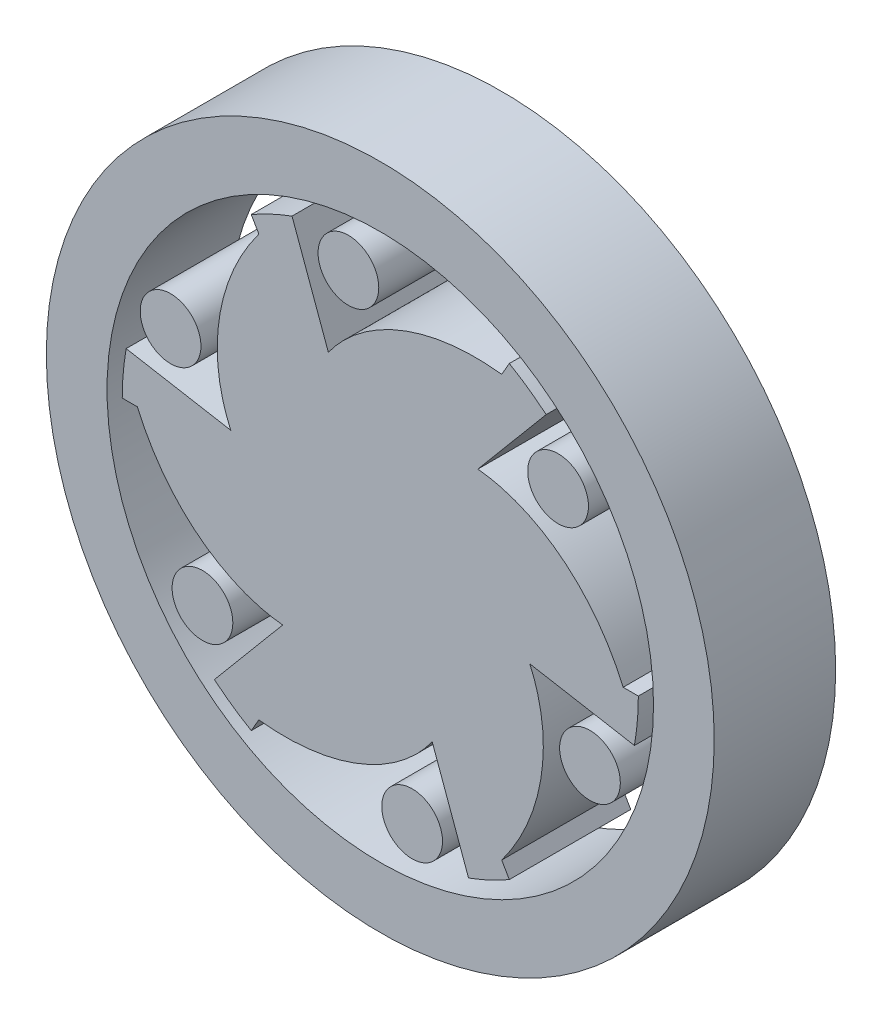
SolidWorks part; units mm, degrees
ref_plane "Front Plane" through (0, 0, 0) normal (0, 0, 1) x (1, 0, 0)
ref_plane "Top Plane" through (0, 0, 0) normal (0, 1, 0) x (1, 0, 0)
ref_plane "Right Plane" through (0, 0, 0) normal (1, 0, 0) x (0, 0, -1)
sketch "Sketch1" plane through (0, 0, 0) normal (0, 0, 1) x (1, 0, 0)
  line L5 (5.7851, 6.8944) -> (0, 0) construction
  line L9 (5.4637, 6.5114) -> (3.2139, 3.8302)
  line L10 (0, 0) -> (4.25, 7.3612)
  line L11 (8, 0) -> (0, 0)
  line L12 (5.5, 9.5263) -> (4.5, 7.7942)
  line L13 (9, 0) -> (11, 0)
  line L14 (4, -6.9282) -> (0, 0)
  line L15 (0, 0) -> (8.5, 0)
  line L16 (9, 0) -> (0, 0) construction
  line L17 (8.3709, -1.476) -> (4.924, -0.8682)
  line L18 (-4, -6.9282) -> (0, 0)
  line L19 (0, 0) -> (4.25, -7.3612)
  line L20 (2.9072, -7.9874) -> (1.7101, -4.6985)
  line L21 (-8, 0) -> (0, 0)
  line L22 (0, 0) -> (-4.25, -7.3612)
  line L23 (-5.4637, -6.5114) -> (-3.2139, -3.8302)
  line L24 (-4, 6.9282) -> (0, 0)
  line L25 (0, 0) -> (-8.5, 0)
  line L26 (-8.3709, 1.476) -> (-4.924, 0.8682)
  line L27 (4, 6.9282) -> (0, 0)
  line L28 (0, 0) -> (-4.25, 7.3612)
  line L29 (-2.9072, 7.9874) -> (-1.7101, 4.6985)
  line L30 (11, 0) -> (9, 0)
  line L31 (4.5, -7.7942) -> (5.5, -9.5263)
  line L32 (5.5, -9.5263) -> (4.5, -7.7942)
  line L33 (-4.5, -7.7942) -> (-5.5, -9.5263)
  line L34 (-5.5, -9.5263) -> (-4.5, -7.7942)
  line L35 (-9, 0) -> (-11, 0)
  line L36 (-11, 0) -> (-9, 0)
  line L37 (-4.5, 7.7942) -> (-5.5, 9.5263)
  line L38 (-5.5, 9.5263) -> (-4.5, 7.7942)
  line L39 (4.5, 7.7942) -> (5.5, 9.5263)
  circle A11 centre (5.8572, 4.594) radius 1
  circle A12 centre (5.8572, 4.594) radius 1.5 construction
  circle A13 centre (0, 0) radius 9 construction
  circle A16 centre (7.4489, 2.7445) radius 1 construction
  circle A17 centre (7.4489, 2.7445) radius 1.5 construction
  arc A18 (4.25, 7.3612) -> (5.4637, 6.5114) centre (0, 0) cw
  circle A19 centre (0, 0) radius 11 construction
  arc A20 (11, 0) -> (5.5, 9.5263) centre (0, 0) ccw
  arc A21 (4.5, 7.7942) -> (9, 0) centre (0, 0) cw
  arc A22 (8.5, 0) -> (8.3709, -1.476) centre (0, 0) cw
  circle A23 centre (6.9071, -2.7754) radius 1
  arc A24 (4.25, -7.3612) -> (2.9072, -7.9874) centre (0, 0) cw
  circle A25 centre (1.0499, -7.3694) radius 1
  arc A26 (-4.25, -7.3612) -> (-5.4637, -6.5114) centre (0, 0) cw
  circle A27 centre (-5.8572, -4.594) radius 1
  arc A28 (-8.5, 0) -> (-8.3709, 1.476) centre (0, 0) cw
  circle A29 centre (-6.9071, 2.7754) radius 1
  arc A30 (-4.25, 7.3612) -> (-2.9072, 7.9874) centre (0, 0) cw
  circle A31 centre (-1.0499, 7.3694) radius 1
  circle A32 centre (6.1012, -5.0787) radius 1.5 construction
  arc A33 (9, 0) -> (4.5, -7.7942) centre (0, 0) cw
  arc A34 (5.5, -9.5263) -> (11, 0) centre (0, 0) ccw
  circle A35 centre (-1.3477, -7.8231) radius 1.5 construction
  arc A36 (4.5, -7.7942) -> (-4.5, -7.7942) centre (0, 0) cw
  arc A37 (-5.5, -9.5263) -> (5.5, -9.5263) centre (0, 0) ccw
  circle A38 centre (-7.4489, -2.7445) radius 1.5 construction
  arc A39 (-4.5, -7.7942) -> (-9, 0) centre (0, 0) cw
  arc A40 (-11, 0) -> (-5.5, -9.5263) centre (0, 0) ccw
  circle A41 centre (-6.1012, 5.0787) radius 1.5 construction
  arc A42 (-9, 0) -> (-4.5, 7.7942) centre (0, 0) cw
  arc A43 (-5.5, 9.5263) -> (-11, 0) centre (0, 0) ccw
  circle A44 centre (1.3477, 7.8231) radius 1.5 construction
  arc A45 (-4.5, 7.7942) -> (4.5, 7.7942) centre (0, 0) cw
  arc A46 (5.5, 9.5263) -> (-5.5, 9.5263) centre (0, 0) ccw
  spline S0 degree 4 poles (8.2297, -0.6031) (8.2177, -0.5709) (8.2166, -0.5602) (8.173, -0.4439) (8.1451, -0.3547) (8.035, -0.0811) (7.9889, 0.0291) (7.8625, 0.3063) (7.7823, 0.4631) (7.676, 0.6656) (7.576, 0.8379) (7.4369, 1.0671) (7.293, 1.2812) (7.1379, 1.4954) (6.9431, 1.7408) (6.7374, 1.9796) (6.4836, 2.244) (6.1868, 2.5153) (5.9146, 2.7339) (5.6732, 2.907) (5.469, 3.0407) (5.2891, 3.1491) (5.1064, 3.2506) (4.9182, 3.3455) (4.7296, 3.4328) (4.5326, 3.5131) (4.3411, 3.5849) (4.1329, 3.65) (3.9452, 3.7046) (3.7172, 3.7543) (3.5507, 3.7891) (3.269, 3.826) (3.1429, 3.8378) (2.8808, 3.8539) (2.8076, 3.8497) (2.71, 3.8512) (2.7092, 3.8498) (2.7012, 3.8499) (2.6959, 3.85) knots 0 0 0 0 0 0.010587 0.021173 0.042347 0.084694 0.112315 0.139937 0.167558 0.19518 0.222801 0.250422 0.305665 0.333287 0.360908 0.416151 0.471394 0.526637 0.572552 0.600173 0.627794 0.655416 0.683037 0.710659 0.73828 0.765902 0.793523 0.821145 0.848766 0.876388 0.904009 0.93163 0.96246 0.993289 0.996645 0.998322 1 1 1 1 1 construction
  spline S1 degree 4 poles (8, 0) (7.9825, 0.0408) (7.9462, 0.1228) (7.8625, 0.3063) (7.7823, 0.4631) (7.676, 0.6656) (7.576, 0.8379) (7.4369, 1.0671) (7.293, 1.2812) (7.1379, 1.4954) (6.9431, 1.7408) (6.7374, 1.9796) (6.4836, 2.244) (6.1868, 2.5153) (5.9146, 2.7339) (5.6732, 2.907) (5.469, 3.0407) (5.2891, 3.1491) (5.1064, 3.2506) (4.9182, 3.3455) (4.7296, 3.4328) (4.5326, 3.5131) (4.3411, 3.5849) (4.1329, 3.65) (3.9452, 3.7046) (3.7172, 3.7543) (3.5507, 3.7891) (3.3454, 3.816) (3.2581, 3.826) (3.2139, 3.8302) knots 0.084694 0.084694 0.084694 0.084694 0.084694 0.112315 0.139937 0.167558 0.19518 0.222801 0.250422 0.305665 0.333287 0.360908 0.416151 0.471394 0.526637 0.572552 0.600173 0.627794 0.655416 0.683037 0.710659 0.73828 0.765902 0.793523 0.821145 0.848766 0.876388 0.904009 0.93163 0.93163 0.93163 0.93163 0.93163
  spline S2 degree 4 poles (3.5925, -7.4286) (3.6144, -7.4022) (3.6231, -7.3959) (3.7021, -7.3) (3.7654, -7.2312) (3.9473, -6.999) (4.0196, -6.904) (4.1965, -6.656) (4.2923, -6.5081) (4.4144, -6.3148) (4.5137, -6.1421) (4.6425, -5.907) (4.7561, -5.6753) (4.864, -5.4339) (4.9791, -5.1426) (5.0831, -4.845) (5.1851, -4.4929) (5.2717, -4.1002) (5.3249, -3.7552) (5.3542, -3.4597) (5.3678, -3.2159) (5.3717, -3.0059) (5.3683, -2.797) (5.3564, -2.5866) (5.3377, -2.3796) (5.3088, -2.1688) (5.2752, -1.9671) (5.2274, -1.7542) (5.1809, -1.5643) (5.1099, -1.3421) (5.0568, -1.1804) (4.9479, -0.9181) (4.895, -0.8029) (4.7779, -0.5679) (4.7377, -0.5066) (4.6903, -0.4214) (4.6887, -0.4213) (4.6847, -0.4144) (4.6822, -0.4098) knots 0 0 0 0 0 0.010587 0.021173 0.042347 0.084694 0.112315 0.139937 0.167558 0.19518 0.222801 0.250422 0.305665 0.333287 0.360908 0.416151 0.471394 0.526637 0.572552 0.600173 0.627794 0.655416 0.683037 0.710659 0.73828 0.765902 0.793523 0.821145 0.848766 0.876388 0.904009 0.93163 0.96246 0.993289 0.996645 0.998322 1 1 1 1 1 construction
  spline S3 degree 4 poles (4, -6.9282) (4.0266, -6.8926) (4.0795, -6.8201) (4.1965, -6.656) (4.2923, -6.5081) (4.4144, -6.3148) (4.5137, -6.1421) (4.6425, -5.907) (4.7561, -5.6753) (4.864, -5.4339) (4.9791, -5.1426) (5.0831, -4.845) (5.1851, -4.4929) (5.2717, -4.1002) (5.3249, -3.7552) (5.3542, -3.4597) (5.3678, -3.2159) (5.3717, -3.0059) (5.3683, -2.797) (5.3564, -2.5866) (5.3377, -2.3796) (5.3088, -2.1688) (5.2752, -1.9671) (5.2274, -1.7542) (5.1809, -1.5643) (5.1099, -1.3421) (5.0568, -1.1804) (4.9774, -0.9892) (4.9424, -0.9086) (4.924, -0.8682) knots 0.084694 0.084694 0.084694 0.084694 0.084694 0.112315 0.139937 0.167558 0.19518 0.222801 0.250422 0.305665 0.333287 0.360908 0.416151 0.471394 0.526637 0.572552 0.600173 0.627794 0.655416 0.683037 0.710659 0.73828 0.765902 0.793523 0.821145 0.848766 0.876388 0.904009 0.93163 0.93163 0.93163 0.93163 0.93163
  spline S4 degree 4 poles (-4.6371, -6.8256) (-4.6032, -6.8313) (-4.5934, -6.8357) (-4.4709, -6.8561) (-4.3797, -6.8766) (-4.0877, -6.918) (-3.9692, -6.9331) (-3.666, -6.9623) (-3.4901, -6.9713) (-3.2616, -6.9804) (-3.0624, -6.98) (-2.7943, -6.9741) (-2.5369, -6.9566) (-2.2739, -6.9293) (-1.964, -6.8833) (-1.6543, -6.8246) (-1.2984, -6.7369) (-0.915, -6.6155) (-0.5897, -6.4891) (-0.3191, -6.3667) (-0.1012, -6.2566) (0.0826, -6.155) (0.2619, -6.0476) (0.4381, -5.932) (0.608, -5.8124) (0.7761, -5.6819) (0.934, -5.552) (1.0946, -5.4042) (1.2357, -5.2689) (1.3927, -5.0964) (1.5061, -4.9696) (1.6789, -4.744) (1.7522, -4.6407) (1.8972, -4.4217) (1.9301, -4.3563) (1.9802, -4.2726) (1.9794, -4.2712) (1.9835, -4.2642) (1.9862, -4.2598) knots 0 0 0 0 0 0.010587 0.021173 0.042347 0.084694 0.112315 0.139937 0.167558 0.19518 0.222801 0.250422 0.305665 0.333287 0.360908 0.416151 0.471394 0.526637 0.572552 0.600173 0.627794 0.655416 0.683037 0.710659 0.73828 0.765902 0.793523 0.821145 0.848766 0.876388 0.904009 0.93163 0.96246 0.993289 0.996645 0.998322 1 1 1 1 1 construction
  spline S5 degree 4 poles (-4, -6.9282) (-3.9559, -6.9334) (-3.8667, -6.943) (-3.666, -6.9623) (-3.4901, -6.9713) (-3.2616, -6.9804) (-3.0624, -6.98) (-2.7943, -6.9741) (-2.5369, -6.9566) (-2.2739, -6.9293) (-1.964, -6.8833) (-1.6543, -6.8246) (-1.2984, -6.7369) (-0.915, -6.6155) (-0.5897, -6.4891) (-0.3191, -6.3667) (-0.1012, -6.2566) (0.0826, -6.155) (0.2619, -6.0476) (0.4381, -5.932) (0.608, -5.8124) (0.7761, -5.6819) (0.934, -5.552) (1.0946, -5.4042) (1.2357, -5.2689) (1.3927, -5.0964) (1.5061, -4.9696) (1.632, -4.8052) (1.6843, -4.7346) (1.7101, -4.6985) knots 0.084694 0.084694 0.084694 0.084694 0.084694 0.112315 0.139937 0.167558 0.19518 0.222801 0.250422 0.305665 0.333287 0.360908 0.416151 0.471394 0.526637 0.572552 0.600173 0.627794 0.655416 0.683037 0.710659 0.73828 0.765902 0.793523 0.821145 0.848766 0.876388 0.904009 0.93163 0.93163 0.93163 0.93163 0.93163
  spline S6 degree 4 poles (-8.2297, 0.6031) (-8.2177, 0.5709) (-8.2166, 0.5602) (-8.173, 0.4439) (-8.1451, 0.3547) (-8.035, 0.0811) (-7.9889, -0.0291) (-7.8625, -0.3063) (-7.7823, -0.4631) (-7.676, -0.6656) (-7.576, -0.8379) (-7.4369, -1.0671) (-7.293, -1.2812) (-7.1379, -1.4954) (-6.9431, -1.7408) (-6.7374, -1.9796) (-6.4836, -2.244) (-6.1868, -2.5153) (-5.9146, -2.7339) (-5.6732, -2.907) (-5.469, -3.0407) (-5.2891, -3.1491) (-5.1064, -3.2506) (-4.9182, -3.3455) (-4.7296, -3.4328) (-4.5326, -3.5131) (-4.3411, -3.5849) (-4.1329, -3.65) (-3.9452, -3.7046) (-3.7172, -3.7543) (-3.5507, -3.7891) (-3.269, -3.826) (-3.1429, -3.8378) (-2.8808, -3.8539) (-2.8076, -3.8497) (-2.71, -3.8512) (-2.7092, -3.8498) (-2.7012, -3.8499) (-2.6959, -3.85) knots 0 0 0 0 0 0.010587 0.021173 0.042347 0.084694 0.112315 0.139937 0.167558 0.19518 0.222801 0.250422 0.305665 0.333287 0.360908 0.416151 0.471394 0.526637 0.572552 0.600173 0.627794 0.655416 0.683037 0.710659 0.73828 0.765902 0.793523 0.821145 0.848766 0.876388 0.904009 0.93163 0.96246 0.993289 0.996645 0.998322 1 1 1 1 1 construction
  spline S7 degree 4 poles (-8, 0) (-7.9825, -0.0408) (-7.9462, -0.1228) (-7.8625, -0.3063) (-7.7823, -0.4631) (-7.676, -0.6656) (-7.576, -0.8379) (-7.4369, -1.0671) (-7.293, -1.2812) (-7.1379, -1.4954) (-6.9431, -1.7408) (-6.7374, -1.9796) (-6.4836, -2.244) (-6.1868, -2.5153) (-5.9146, -2.7339) (-5.6732, -2.907) (-5.469, -3.0407) (-5.2891, -3.1491) (-5.1064, -3.2506) (-4.9182, -3.3455) (-4.7296, -3.4328) (-4.5326, -3.5131) (-4.3411, -3.5849) (-4.1329, -3.65) (-3.9452, -3.7046) (-3.7172, -3.7543) (-3.5507, -3.7891) (-3.3454, -3.816) (-3.2581, -3.826) (-3.2139, -3.8302) knots 0.084694 0.084694 0.084694 0.084694 0.084694 0.112315 0.139937 0.167558 0.19518 0.222801 0.250422 0.305665 0.333287 0.360908 0.416151 0.471394 0.526637 0.572552 0.600173 0.627794 0.655416 0.683037 0.710659 0.73828 0.765902 0.793523 0.821145 0.848766 0.876388 0.904009 0.93163 0.93163 0.93163 0.93163 0.93163
  spline S8 degree 4 poles (-3.5925, 7.4286) (-3.6144, 7.4022) (-3.6231, 7.3959) (-3.7021, 7.3) (-3.7654, 7.2312) (-3.9473, 6.999) (-4.0196, 6.904) (-4.1965, 6.656) (-4.2923, 6.5081) (-4.4144, 6.3148) (-4.5137, 6.1421) (-4.6425, 5.907) (-4.7561, 5.6753) (-4.864, 5.4339) (-4.9791, 5.1426) (-5.0831, 4.845) (-5.1851, 4.4929) (-5.2717, 4.1002) (-5.3249, 3.7552) (-5.3542, 3.4597) (-5.3678, 3.2159) (-5.3717, 3.0059) (-5.3683, 2.797) (-5.3564, 2.5866) (-5.3377, 2.3796) (-5.3088, 2.1688) (-5.2752, 1.9671) (-5.2274, 1.7542) (-5.1809, 1.5643) (-5.1099, 1.3421) (-5.0568, 1.1804) (-4.9479, 0.9181) (-4.895, 0.8029) (-4.7779, 0.5679) (-4.7377, 0.5066) (-4.6903, 0.4214) (-4.6887, 0.4213) (-4.6847, 0.4144) (-4.6822, 0.4098) knots 0 0 0 0 0 0.010587 0.021173 0.042347 0.084694 0.112315 0.139937 0.167558 0.19518 0.222801 0.250422 0.305665 0.333287 0.360908 0.416151 0.471394 0.526637 0.572552 0.600173 0.627794 0.655416 0.683037 0.710659 0.73828 0.765902 0.793523 0.821145 0.848766 0.876388 0.904009 0.93163 0.96246 0.993289 0.996645 0.998322 1 1 1 1 1 construction
  spline S9 degree 4 poles (-4, 6.9282) (-4.0266, 6.8926) (-4.0795, 6.8201) (-4.1965, 6.656) (-4.2923, 6.5081) (-4.4144, 6.3148) (-4.5137, 6.1421) (-4.6425, 5.907) (-4.7561, 5.6753) (-4.864, 5.4339) (-4.9791, 5.1426) (-5.0831, 4.845) (-5.1851, 4.4929) (-5.2717, 4.1002) (-5.3249, 3.7552) (-5.3542, 3.4597) (-5.3678, 3.2159) (-5.3717, 3.0059) (-5.3683, 2.797) (-5.3564, 2.5866) (-5.3377, 2.3796) (-5.3088, 2.1688) (-5.2752, 1.9671) (-5.2274, 1.7542) (-5.1809, 1.5643) (-5.1099, 1.3421) (-5.0568, 1.1804) (-4.9774, 0.9892) (-4.9424, 0.9086) (-4.924, 0.8682) knots 0.084694 0.084694 0.084694 0.084694 0.084694 0.112315 0.139937 0.167558 0.19518 0.222801 0.250422 0.305665 0.333287 0.360908 0.416151 0.471394 0.526637 0.572552 0.600173 0.627794 0.655416 0.683037 0.710659 0.73828 0.765902 0.793523 0.821145 0.848766 0.876388 0.904009 0.93163 0.93163 0.93163 0.93163 0.93163
  spline S10 degree 4 poles (4.6371, 6.8256) (4.6032, 6.8313) (4.5934, 6.8357) (4.4709, 6.8561) (4.3797, 6.8766) (4.0877, 6.918) (3.9692, 6.9331) (3.666, 6.9623) (3.4901, 6.9713) (3.2616, 6.9804) (3.0624, 6.98) (2.7943, 6.9741) (2.5369, 6.9566) (2.2739, 6.9293) (1.964, 6.8833) (1.6543, 6.8246) (1.2984, 6.7369) (0.915, 6.6155) (0.5897, 6.4891) (0.3191, 6.3667) (0.1012, 6.2566) (-0.0826, 6.155) (-0.2619, 6.0476) (-0.4381, 5.932) (-0.608, 5.8124) (-0.7761, 5.6819) (-0.934, 5.552) (-1.0946, 5.4042) (-1.2357, 5.2689) (-1.3927, 5.0964) (-1.5061, 4.9696) (-1.6789, 4.744) (-1.7522, 4.6407) (-1.8972, 4.4217) (-1.9301, 4.3563) (-1.9802, 4.2726) (-1.9794, 4.2712) (-1.9835, 4.2642) (-1.9862, 4.2598) knots 0 0 0 0 0 0.010587 0.021173 0.042347 0.084694 0.112315 0.139937 0.167558 0.19518 0.222801 0.250422 0.305665 0.333287 0.360908 0.416151 0.471394 0.526637 0.572552 0.600173 0.627794 0.655416 0.683037 0.710659 0.73828 0.765902 0.793523 0.821145 0.848766 0.876388 0.904009 0.93163 0.96246 0.993289 0.996645 0.998322 1 1 1 1 1 construction
  spline S11 degree 4 poles (4, 6.9282) (3.9559, 6.9334) (3.8667, 6.943) (3.666, 6.9623) (3.4901, 6.9713) (3.2616, 6.9804) (3.0624, 6.98) (2.7943, 6.9741) (2.5369, 6.9566) (2.2739, 6.9293) (1.964, 6.8833) (1.6543, 6.8246) (1.2984, 6.7369) (0.915, 6.6155) (0.5897, 6.4891) (0.3191, 6.3667) (0.1012, 6.2566) (-0.0826, 6.155) (-0.2619, 6.0476) (-0.4381, 5.932) (-0.608, 5.8124) (-0.7761, 5.6819) (-0.934, 5.552) (-1.0946, 5.4042) (-1.2357, 5.2689) (-1.3927, 5.0964) (-1.5061, 4.9696) (-1.632, 4.8052) (-1.6843, 4.7346) (-1.7101, 4.6985) knots 0.084694 0.084694 0.084694 0.084694 0.084694 0.112315 0.139937 0.167558 0.19518 0.222801 0.250422 0.305665 0.333287 0.360908 0.416151 0.471394 0.526637 0.572552 0.600173 0.627794 0.655416 0.683037 0.710659 0.73828 0.765902 0.793523 0.821145 0.848766 0.876388 0.904009 0.93163 0.93163 0.93163 0.93163 0.93163
  dimension "D1" = 50
  dimension "D2" = 6
  dimension "D3" = 6
extrude "Boss-Extrude1" add sketch "Sketch1" along normal blind 4 contours L33 A37 L31 A36 | L35 A40 L33 A39 | A27 | L21 S7 L23 A26 L22 L18 | L18 S5 L20 A24 L19 L14 | L14 S3 L17 A22 L15 L11 | L31 A34 L13 A33 | L12 A21 L13 A20 | L37 A43 L35 A42 | L24 S9 L26 A28 L25 L21 | A29 | L11 S1 L9 A18 L10 | A23 | L10 S11 L29 A30 L28 L24 | A31 | A25 | A11 | L12 A46 L37 A45
equation "\"RampRise\"= - \"Clearance\" * 2 - 2"
equation "\"RollerD\"= 2"
equation "\"RingIR\"= \"RingID\" / 2"
equation "\"Clearance\" = 0.5"
equation "\"RingID\"= \"RingOD\" - 2 * 2"
equation "\"RingOD\"= 22"
equation "\"RampStartR\" = \"RingIR\" - \"RollerD\" + 1"
equation "\"WallSpan\"= 10"
